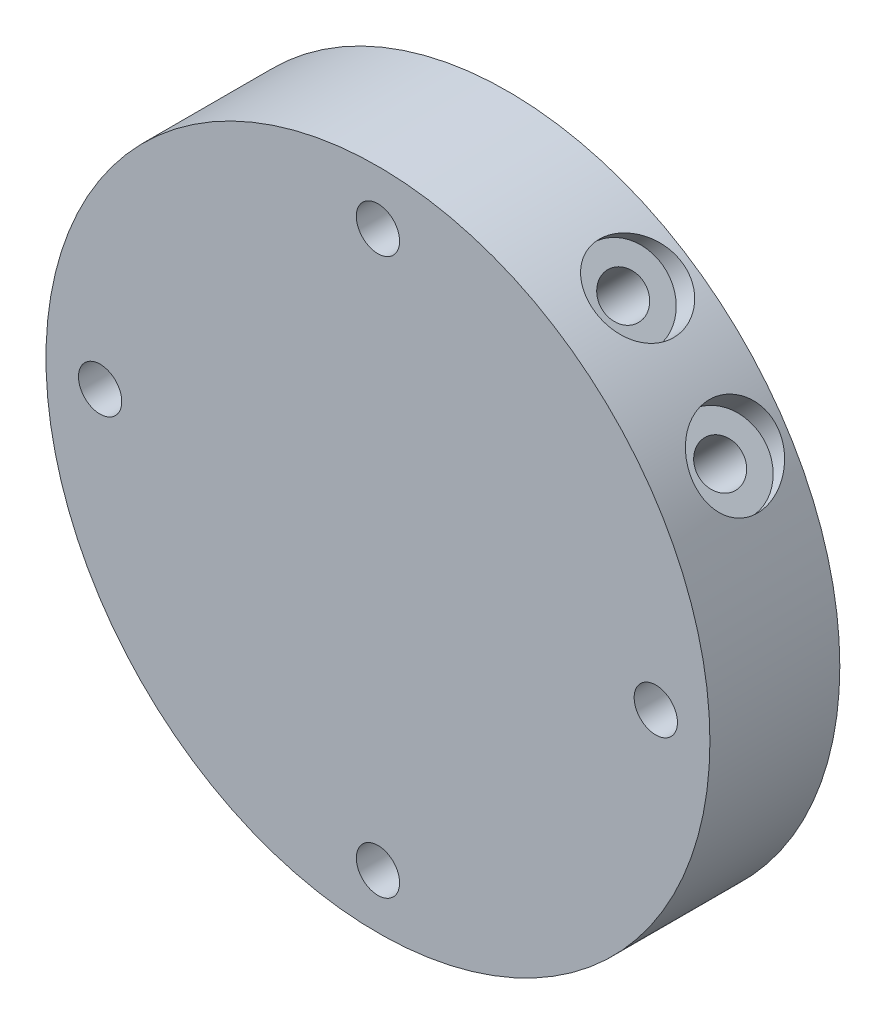
SolidWorks part; units mm, degrees
ref_plane "前视基准面" through (0, 0, 0) normal (0, 0, 1) x (1, 0, 0)
ref_plane "上视基准面" through (0, 0, 0) normal (0, 1, 0) x (1, 0, 0)
ref_plane "右视基准面" through (0, 0, 0) normal (1, 0, 0) x (0, 0, -1)
other "Configuration Table"
sketch "草图1" plane through (0, 0, 0) normal (0, 0, 1) x (1, 0, 0)
  line L9 (2.4749, 15.4149) -> (-15.4149, -2.4749)
  line L10 (2.4749, 15.4149) -> (15.4149, 2.4749)
  line L11 (-15.4149, -2.4749) -> (-2.4749, -15.4149)
  line L12 (15.4149, 2.4749) -> (-2.4749, -15.4149)
  line L13 (2.4749, 15.4149) -> (-2.4749, -15.4149) construction
  line L14 (-15.4149, -2.4749) -> (15.4149, 2.4749) construction
  line L15 (-19.25, 0) -> (0, -19.25) construction
  line L16 (8.4853, 8.4853) -> (0, 0) construction
  circle A0 centre (0, 19.25) radius 1.5
  circle A1 centre (19.25, 0) radius 1.5
  circle A2 centre (0, -19.25) radius 1.5
  circle A3 centre (-19.25, 0) radius 1.5
  circle A5 centre (8.4853, 8.4853) radius 3.9 construction
  circle A6 centre (11.5911, -3.1058) radius 3.9
  circle A13 centre (0, 0) radius 23
  circle A14 centre (3.1058, -11.5911) radius 3.9
  circle A15 centre (-8.4853, -8.4853) radius 3.9 construction
  circle A16 centre (-11.5911, 3.1058) radius 3.9
  circle A17 centre (-3.1058, 11.5911) radius 3.9
  point P12 (0, 0)
  point P17 (-8.4695, 15.5171)
  point P18 (0, 0)
  point P19 (0, 0)
  point P29 (0, 0)
  dimension "D1" = 3
  dimension "D4" = 18.3
  dimension "D8" = 46
  dimension "D6" = 7.8
  dimension "D2" = 19.25
  dimension "D5" = 25.3
  dimension "D7" = 12
  dimension "D3" = 4
  dimension "D9" = 6
extrude "凸台-拉伸1" add sketch "草图1" along normal blind 7
fillet "圆角1" radius 1.5 1 edges at (0.3867, 13.3267, 3.5)
fillet "圆角2" radius 1.5 7 edges at (-8.0986, 4.8415, 3.5) (-13.3267, -0.3867, 3.5) (-0.3867, -13.3267, 3.5) (4.8415, -8.0986, 3.5) (8.0986, -4.8415, 3.5) (13.3267, 0.3867, 3.5) (-4.8415, 8.0986, 3.5)
sketch "草图3" plane through (0, 0, 7) normal (0, 0, 1) x (1, 0, 0)
  line L0 (1.5866, 14.5267) -> (-14.5267, -1.5866)
  line L1 (-1.5866, -14.5267) -> (14.5267, 1.5866)
  line L8 (-14.5267, -1.5866) -> (-15.4149, -2.4749)
  line L9 (-6.0414, 6.8986) -> (-6.8986, 6.0414)
  line L10 (2.4749, 15.4149) -> (1.5866, 14.5267)
  line L11 (15.4149, 2.4749) -> (2.4749, 15.4149)
  line L12 (14.5267, 1.5866) -> (15.4149, 2.4749)
  line L13 (6.0414, -6.8986) -> (6.8986, -6.0414)
  line L14 (-2.4749, -15.4149) -> (-1.5866, -14.5267)
  line L15 (-15.4149, -2.4749) -> (-2.4749, -15.4149)
  line L16 (-14.5267, -1.5866) -> (-15.4149, -2.4749)
  line L17 (-6.0414, 6.8986) -> (-6.8986, 6.0414)
  line L18 (2.4749, 15.4149) -> (1.5866, 14.5267)
  line L19 (15.4149, 2.4749) -> (2.4749, 15.4149)
  line L20 (14.5267, 1.5866) -> (15.4149, 2.4749)
  line L21 (6.0414, -6.8986) -> (6.8986, -6.0414)
  line L22 (-2.4749, -15.4149) -> (-1.5866, -14.5267)
  line L23 (-15.4149, -2.4749) -> (-2.4749, -15.4149)
  circle A1 centre (0, 0) radius 23
  circle A2 centre (0, 0) radius 23
  circle A3 centre (0, 19.25) radius 1.5
  circle A4 centre (0, 19.25) radius 1.5
  circle A5 centre (19.25, 0) radius 1.5
  circle A6 centre (19.25, 0) radius 1.5
  circle A7 centre (0, -19.25) radius 1.5
  circle A8 centre (0, -19.25) radius 1.5
  circle A9 centre (-19.25, 0) radius 1.5
  circle A10 centre (-19.25, 0) radius 1.5
  arc A14 (-14.5267, -1.5866) -> (-14.4773, 0.4829) centre (-15.5874, -0.526) ccw
  arc A15 (-8.9681, 5.992) -> (-14.4773, 0.4829) centre (-11.5911, 3.1058) ccw
  arc A16 (-8.9681, 5.992) -> (-6.8986, 6.0414) centre (-7.9593, 7.1021) ccw
  arc A17 (-6.0414, 6.8986) -> (-5.992, 8.9681) centre (-7.1021, 7.9593) ccw
  arc A18 (-0.4829, 14.4773) -> (-5.992, 8.9681) centre (-3.1058, 11.5911) ccw
  arc A19 (-0.4829, 14.4773) -> (1.5866, 14.5267) centre (0.526, 15.5874) ccw
  arc A20 (14.5267, 1.5866) -> (14.4773, -0.4829) centre (15.5874, 0.526) ccw
  arc A21 (8.9681, -5.992) -> (14.4773, -0.4829) centre (11.5911, -3.1058) ccw
  arc A22 (8.9681, -5.992) -> (6.8986, -6.0414) centre (7.9593, -7.1021) ccw
  arc A23 (6.0414, -6.8986) -> (5.992, -8.9681) centre (7.1021, -7.9593) ccw
  arc A24 (0.4829, -14.4773) -> (5.992, -8.9681) centre (3.1058, -11.5911) ccw
  arc A25 (0.4829, -14.4773) -> (-1.5866, -14.5267) centre (-0.526, -15.5874) ccw
  arc A26 (-14.5267, -1.5866) -> (-14.4773, 0.4829) centre (-15.5874, -0.526) ccw
  arc A27 (-8.9681, 5.992) -> (-14.4773, 0.4829) centre (-11.5911, 3.1058) ccw
  arc A28 (-8.9681, 5.992) -> (-6.8986, 6.0414) centre (-7.9593, 7.1021) ccw
  arc A29 (-6.0414, 6.8986) -> (-5.992, 8.9681) centre (-7.1021, 7.9593) ccw
  arc A30 (-0.4829, 14.4773) -> (-5.992, 8.9681) centre (-3.1058, 11.5911) ccw
  arc A31 (-0.4829, 14.4773) -> (1.5866, 14.5267) centre (0.526, 15.5874) ccw
  arc A32 (14.5267, 1.5866) -> (14.4773, -0.4829) centre (15.5874, 0.526) ccw
  arc A33 (8.9681, -5.992) -> (14.4773, -0.4829) centre (11.5911, -3.1058) ccw
  arc A34 (8.9681, -5.992) -> (6.8986, -6.0414) centre (7.9593, -7.1021) ccw
  arc A35 (6.0414, -6.8986) -> (5.992, -8.9681) centre (7.1021, -7.9593) ccw
  arc A36 (0.4829, -14.4773) -> (5.992, -8.9681) centre (3.1058, -11.5911) ccw
  arc A37 (0.4829, -14.4773) -> (-1.5866, -14.5267) centre (-0.526, -15.5874) ccw
  arc M27 (-14.5267, -1.5866) -> (-14.4773, 0.4829) centre (-15.5874, -0.526) ccw
  arc M28 (-14.4773, 0.4829) -> (-8.9681, 5.992) centre (-11.5911, 3.1058) cw
  arc M29 (-8.9681, 5.992) -> (-6.8986, 6.0414) centre (-7.9593, 7.1021) ccw
  arc M31 (-6.0414, 6.8986) -> (-5.992, 8.9681) centre (-7.1021, 7.9593) ccw
  arc M32 (-5.992, 8.9681) -> (-0.4829, 14.4773) centre (-3.1058, 11.5911) cw
  arc M33 (-0.4829, 14.4773) -> (1.5866, 14.5267) centre (0.526, 15.5874) ccw
  arc M37 (14.5267, 1.5866) -> (14.4773, -0.4829) centre (15.5874, 0.526) ccw
  arc M38 (14.4773, -0.4829) -> (8.9681, -5.992) centre (11.5911, -3.1058) cw
  arc M39 (8.9681, -5.992) -> (6.8986, -6.0414) centre (7.9593, -7.1021) ccw
  arc M41 (6.0414, -6.8986) -> (5.992, -8.9681) centre (7.1021, -7.9593) ccw
  arc M42 (5.992, -8.9681) -> (0.4829, -14.4773) centre (3.1058, -11.5911) cw
  arc M43 (0.4829, -14.4773) -> (-1.5866, -14.5267) centre (-0.526, -15.5874) ccw
  dimension "D1" = 0
  dimension "D2" = 0
  dimension "D3" = 0
  dimension "D4" = 0
  dimension "D5" = 0
  dimension "D6" = 0
extrude "凸台-拉伸2" add sketch "草图3" against normal blind 2 contours L0 M29 M28 M27 | L0 M33 M32 M31 | L1 M39 M38 M37 | L1 M43 M42 M41
fillet "圆角3" radius 1 4 edges at (15.4149, 2.4749, 3.5) (2.4749, 15.4149, 3.5) (-15.4149, -2.4749, 3.5) (-2.4749, -15.4149, 3.5)
sketch "草图4" plane through (0, 0, 0) normal (0, 0, -1) x (-1, 0, 0)
  circle A0 centre (0, -19.25) radius 1.5 construction
  circle A1 centre (19.25, 0) radius 1.5 construction
  circle A2 centre (0, 19.25) radius 1.5 construction
  circle A3 centre (-19.25, 0) radius 1.5 construction
  circle A4 centre (0, -19.25) radius 1.5
  circle A5 centre (19.25, 0) radius 1.5
  circle A6 centre (0, 19.25) radius 1.5
  circle A7 centre (-19.25, 0) radius 1.5
  circle A8 centre (-19.25, 0) radius 3.25
  circle A9 centre (0, 19.25) radius 3.25
  circle A10 centre (19.25, 0) radius 3.25
  circle A11 centre (0, -19.25) radius 3.25
  dimension "D1" = 1.75
extrude "切除-拉伸1" cut sketch "草图4" against normal blind 4
sketch "草图5" plane through (0, 0, 7) normal (0, 0, 1) x (1, 0, 0)
  circle A0 centre (-19.25, 0) radius 1.5 construction
  circle A1 centre (0, 0) radius 23
  circle A2 centre (0, 0) radius 23
  circle A3 centre (0, -19.25) radius 1.5 construction
  circle A4 centre (19.25, 0) radius 1.5 construction
  circle A5 centre (0, 19.25) radius 1.5 construction
  circle A6 centre (-19.25, 0) radius 1.5
  circle A7 centre (0, -19.25) radius 1.5
  circle A8 centre (19.25, 0) radius 1.5
  circle A9 centre (0, 19.25) radius 1.5
  dimension "D1" = 0
extrude "凸台-拉伸3" add sketch "草图5" along normal blind 2
sketch "草图6" plane through (8.9449, 8.9449, 0) normal (-0.7071, -0.7071, 0) x (0, 0, 1)
  line L0 (0, 0) -> (7, 0) construction
  line L1 (7, 8.15) -> (7, -8.15) construction
  line L3 (3.5, 4.75) -> (3.5, 0) construction
  circle A0 centre (3.5, 4.75) radius 1.5
  circle A1 centre (3.5, -4.75) radius 1.5
  point P8 (3.446, 0)
  point P10 (0, 0)
  dimension "D1" = 3
  dimension "D2" = 9.5
extrude "切除-拉伸2" cut sketch "草图6" against normal through all and the other way through all
ref_plane "基准面1" through (-16.2635, -16.2635, 0) normal (-0.7071, -0.7071, 0) x (-0.7071, 0.7071, 0)
sketch "草图7" plane through (-16.2635, -16.2635, 0) normal (-0.7071, -0.7071, 0) x (-0.7071, 0.7071, 0)
  circle A0 centre (4.75, -3.5) radius 1.5 construction
  circle A1 centre (-4.75, -3.5) radius 1.5 construction
  circle A2 centre (4.75, -3.5) radius 1.5
  circle A3 centre (-4.75, -3.5) radius 1.5
  circle A4 centre (-4.75, -3.5) radius 3
  circle A5 centre (4.75, -3.5) radius 3
  dimension "D1" = 6
  dimension "D2" = 6
extrude "切除-拉伸3" cut sketch "草图7" against normal blind 2
ref_plane "基准面2" through (0, 0, 0) normal (0.7071, 0.7071, 0) x (0.7071, -0.7071, 0)
mirror "镜向1" about plane through (0, 0, 0) normal (0.7071, 0.7071, 0) of "切除-拉伸3"
